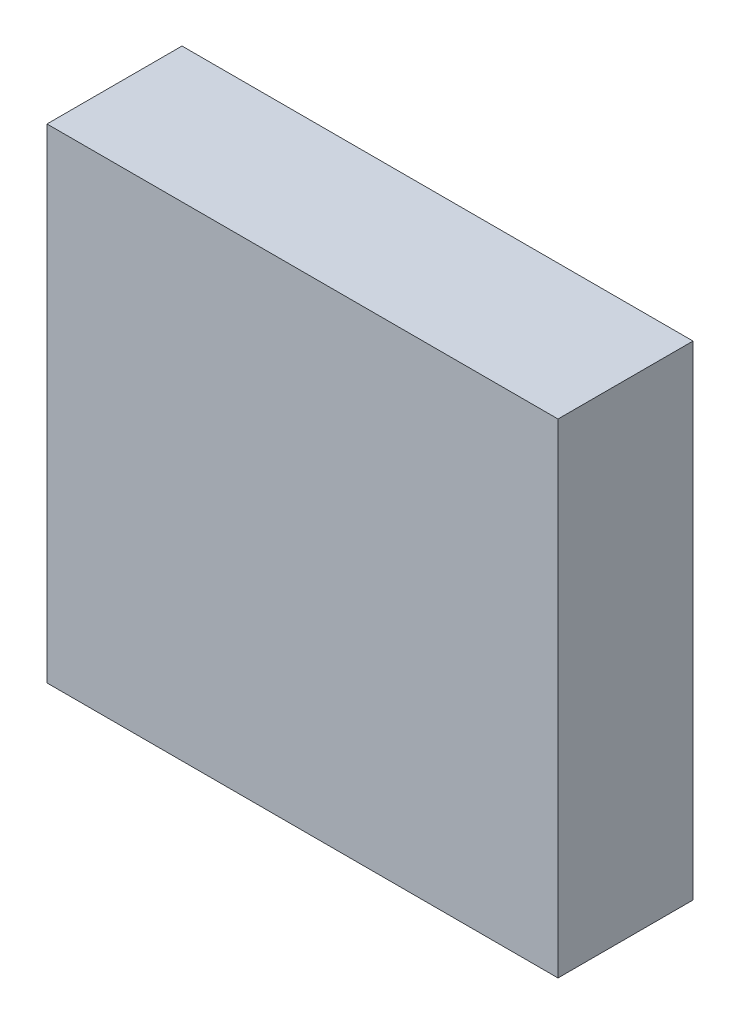
SolidWorks part; units mm, degrees
ref_plane "Front Plane" through (0, 0, 0) normal (0, 0, 1) x (1, 0, 0)
ref_plane "Top Plane" through (0, 0, 0) normal (0, 1, 0) x (1, 0, 0)
ref_plane "Right Plane" through (0, 0, 0) normal (1, 0, 0) x (0, 0, -1)
sketch "Sketch1" plane through (0, 0, 0) normal (0, 0, 1) x (1, 0, 0)
  line L1 (47.5, 45) -> (-47.5, 45)
  line L2 (47.5, 45) -> (47.5, -45)
  line L3 (47.5, -45) -> (-47.5, -45)
  line L4 (-47.5, 45) -> (-47.5, -45)
  line L5 (47.5, 45) -> (-47.5, -45) construction
  line L6 (47.5, -45) -> (-47.5, 45) construction
  point P0 (0, 0)
  dimension "D1" = 90
  dimension "D2" = 95
extrude "Boss-Extrude1" add sketch "Sketch1" along normal blind 25.1
shell "Shell1" thickness 7.82
sketch "Sketch2" plane through (0, 0, 25.1) normal (0, 0, 1) x (1, 0, 0)
  point P0 (0, 0)
